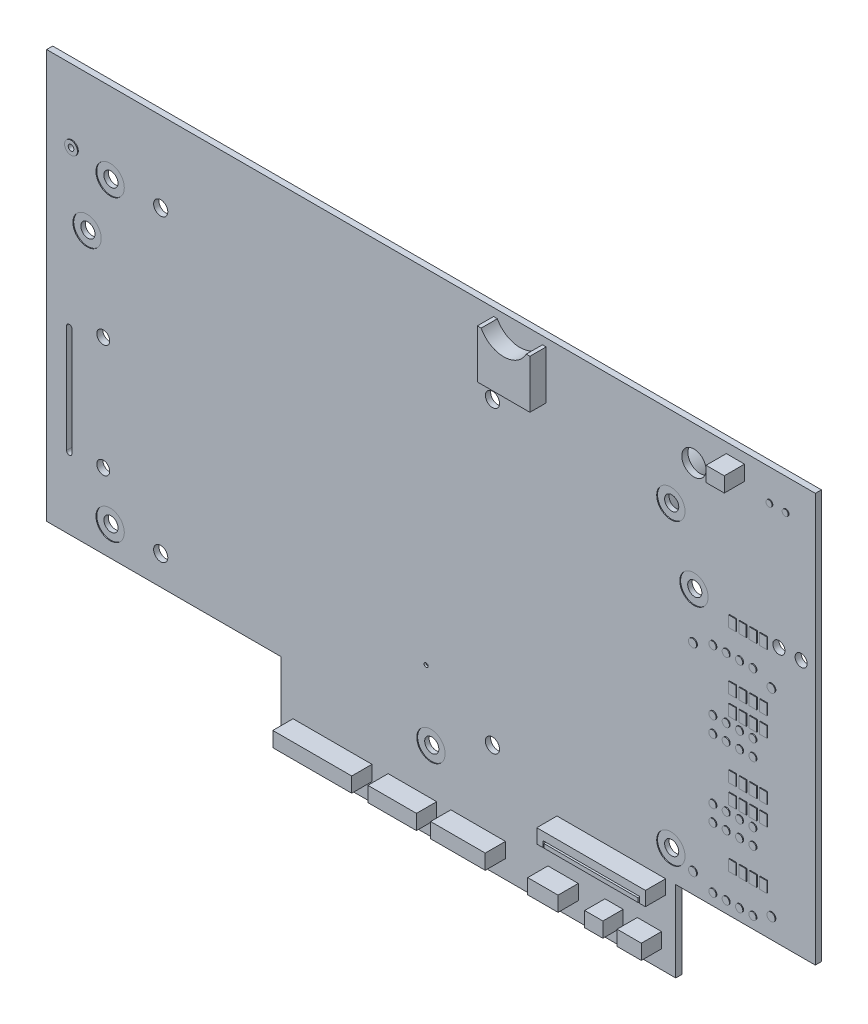
SolidWorks part; units mm, degrees
ref_plane "Face" through (0, 0, 0) normal (0, 0, 1) x (1, 0, 0)
ref_plane "Dessus" through (0, 0, 0) normal (0, 1, 0) x (1, 0, 0)
ref_plane "Droite" through (0, 0, 0) normal (1, 0, 0) x (0, 0, -1)
sketch "Esquisse1" plane through (0, 0, 0) normal (0, 0, 1) x (1, 0, 0)
  line L2 (122.1423, -27.4132) -> (122.1423, 73.5868)
  line L4 (-67.8577, 73.5868) -> (-67.8577, -27.4132)
  line L8 (122.1423, 73.5868) -> (-67.8577, 73.5868)
  line L9 (-67.8577, -27.4132) -> (-9.9458, -27.4132)
  line L10 (-9.9458, -27.4132) -> (-9.9458, -47.4132)
  line L11 (-9.9458, -47.4132) -> (87.6423, -47.4132)
  line L12 (87.6423, -47.4132) -> (87.6423, -27.4132)
  line L13 (87.6423, -27.4132) -> (122.1423, -27.4132)
extrude "Base-Extrusion" add sketch "Esquisse1" along normal blind 1.5
sketch "Esquisse2" plane through (0, 0, 0) normal (0, 0, -1) x (-1, 0, 0)
  circle A0 centre (-86.4423, 53.5868) radius 1.75
  circle A1 centre (52.1577, 53.5868) radius 1.75
  circle A2 centre (52.1577, -20.2132) radius 1.75
  circle A3 centre (-86.4423, -20.2132) radius 1.75
  dimension "D1" = 3.5
  dimension "D2" = 3.5
  dimension "D3" = 3.5
  dimension "D4" = 3.5
extrude "Enlèv. mat.-Extru.1" cut sketch "Esquisse2" against normal blind 2
sketch "Esquisse5" plane through (0, 0, 1.5) normal (0, 0, 1) x (1, 0, 0)
  line L0 (122.1423, -27.4132) -> (122.1423, 73.5868) construction
  line L2 (27.1423, 73.0868) -> (27.1423, -57.4247) construction
  line L3 (122.1423, 73.5868) -> (-67.8577, 73.5868) construction
  circle A0 centre (92.1423, 38.0868) radius 1.75
  circle A1 centre (-57.8577, 39.8368) radius 1.75
  circle A2 centre (27.1423, -27.9132) radius 1.75
  dimension "D1" = 30
  dimension "D3" = 3.5
  dimension "D4" = 66
  dimension "D5" = 3.5
  dimension "D6" = 3.5
  dimension "D2" = 35.5
extrude "Enlèv. mat.-Extru.2" cut sketch "Esquisse5" against normal blind 3
sketch "Esquisse7" plane through (0, 0, 0) normal (0, 0, -1) x (-1, 0, 0)
  line L0 (-73.1423, 95.3031) -> (-73.1423, -81.5415) construction
  line L1 (-122.1423, -27.4132) -> (-122.1423, 73.5868) construction
  line L2 (-45.1037, 46.0868) -> (-133.1932, 46.0868) construction
  line L4 (-122.1423, 73.5868) -> (67.8577, 73.5868) construction
  circle A0 centre (-73.1423, 46.0868) radius 8
  dimension "D4" = 16
  dimension "D2" = 27.5
  dimension "D1" = 49
extrude "Boss.-Extru.1" add sketch "Esquisse7" along normal blind 14.5
sketch "Esquisse10" plane through (0, 0, 1.5) normal (0, 0, 1) x (1, 0, 0)
  circle A0 centre (25.9423, -11.2859) radius 0.5
extrude "Enlèv. mat.-Extru.4" cut sketch "Esquisse10" against normal blind 0.5
sketch "Esquisse15" plane through (0, 0, 1.5) normal (0, 0, 1) x (1, 0, 0)
  line L0 (43.5486, 71.6579) -> (42.6021, 71.6579)
  line L2 (55.6021, 71.6579) -> (55.6021, 59.6579)
  line L3 (42.6021, 71.6579) -> (42.6021, 59.6579)
  line L4 (42.6021, 59.6579) -> (55.6021, 59.6579)
  line L6 (55.6021, 71.6579) -> (54.6958, 71.6579)
  arc A1 (43.5486, 71.6579) -> (54.6958, 71.6579) centre (49.1222, 74.5868) ccw
  dimension "D2" = 6.2963
  dimension "D1" = 13
  dimension "D3" = 14.9289
extrude "Boss.-Extru.6" add sketch "Esquisse15" along normal blind 4
sketch "Esquisse16" plane through (0, 0, 1.5) normal (0, 0, 1) x (1, 0, 0)
  line L0 (58.2923, -30.9132) -> (59.7923, -30.9132)
  line L1 (85.1423, -30.9132) -> (85.1423, -27.4132)
  line L2 (58.2923, -30.9132) -> (58.2923, -27.4132)
  line L3 (58.2923, -27.4132) -> (85.1423, -27.4132)
  line L6 (59.7923, -30.9132) -> (59.7923, -29.4132)
  line L7 (59.7923, -29.4132) -> (83.6423, -29.4132)
  line L8 (83.6423, -29.4132) -> (83.6423, -30.9132)
  line L9 (60.0541, -30.9132) -> (60.0541, -29.9132)
  line L10 (60.0541, -29.9132) -> (83.3602, -29.9132)
  line L11 (83.3602, -29.9132) -> (83.3602, -30.9132)
  line L12 (60.0541, -30.9132) -> (83.3602, -30.9132)
  line L13 (83.6423, -30.9132) -> (85.1423, -30.9132)
  line L14 (-9.9458, -47.4132) -> (87.6423, -47.4132) construction
  line L15 (87.6423, -47.4132) -> (87.6423, -27.4132) construction
  dimension "D1" = 26.85
  dimension "D3" = 3.5
  dimension "D4" = 2.5
  dimension "D5" = 1.5
  dimension "D6" = 1.5
  dimension "D7" = 1
  dimension "D8" = 2
  dimension "D9" = 16.5
extrude "Boss.-Extru.7" add sketch "Esquisse16" along normal blind 5
sketch "Esquisse17" plane through (0, 0, 0) normal (0, 0, -1) x (-1, 0, 0)
  circle A0 centre (-27.1423, -24.4132) radius 8
  circle A1 centre (-92.1423, 41.5868) radius 8
  circle A2 centre (57.8577, 43.3368) radius 8
extrude "Enlèv. mat.-Extru.6" cut sketch "Esquisse17" against normal blind 0.2
sketch "Esquisse18" plane through (0, 0, 0) normal (0, 0, -1) x (-1, 0, 0)
  circle A0 centre (-86.4423, 53.5868) radius 3.5
  circle A3 centre (52.1577, 53.5868) radius 3.5
  circle A4 centre (52.1577, -20.2132) radius 3.5
  circle A7 centre (-86.4423, -20.2132) radius 3.5
extrude "Enlèv. mat.-Extru.7" cut sketch "Esquisse18" against normal blind 0.2
sketch "Esquisse19" plane through (0, 0, 1.5) normal (0, 0, 1) x (1, 0, 0)
  circle A0 centre (-52.1577, 53.5868) radius 3.5
  circle A3 centre (86.4423, 53.5868) radius 3.5
  circle A4 centre (92.1423, 38.0868) radius 3.5
  circle A5 centre (86.4423, -20.2132) radius 3.5
  circle A7 centre (27.1423, -27.9132) radius 3.5
  circle A9 centre (-52.1577, -20.2132) radius 3.5
  circle A10 centre (-57.8577, 39.8368) radius 3.5
extrude "Enlèv. mat.-Extru.8" cut sketch "Esquisse19" against normal blind 0.2
sketch "Esquisse22" plane through (0, 0, 1.5) normal (0, 0, 1) x (1, 0, 0)
  line L0 (56.0542, -39.2132) -> (56.0542, -42.9132)
  line L2 (56.0542, -39.2132) -> (63.5542, -39.2132)
  line L3 (56.0542, -42.9132) -> (63.5542, -42.9132)
  line L4 (63.5542, -39.2132) -> (63.5542, -42.9132)
  line L5 (100.1423, 71.0868) -> (100.1423, 67.3868)
  line L6 (78.1423, -39.2132) -> (78.1423, -42.9132)
  line L7 (84.1423, -39.2132) -> (84.1423, -42.9132)
  line L8 (78.1423, -39.2132) -> (84.1423, -39.2132)
  line L9 (78.1423, -42.9132) -> (84.1423, -42.9132)
  line L10 (100.1423, 71.0868) -> (104.6423, 71.0868)
  line L11 (100.1423, 67.3868) -> (104.6423, 67.3868)
  line L12 (104.6423, 71.0868) -> (104.6423, 67.3868)
  line L13 (122.1423, -27.4132) -> (122.1423, 73.5868) construction
  line L17 (32.0542, -39.2132) -> (32.0542, -42.9132)
  line L18 (32.0542, -39.2132) -> (45.5542, -39.2132)
  line L19 (32.0542, -42.9132) -> (45.5542, -42.9132)
  line L20 (45.5542, -39.2132) -> (45.5542, -42.9132)
  line L21 (70.1423, -39.2132) -> (70.1423, -42.9132)
  line L22 (70.1423, -39.2132) -> (74.6423, -39.2132)
  line L23 (70.1423, -42.9132) -> (74.6423, -42.9132)
  line L24 (74.6423, -39.2132) -> (74.6423, -42.9132)
  line L25 (28.5542, -39.2132) -> (16.5542, -39.2132)
  line L26 (28.5542, -39.2132) -> (28.5542, -42.9132)
  line L27 (28.5542, -42.9132) -> (16.5542, -42.9132)
  line L28 (16.5542, -39.2132) -> (16.5542, -42.9132)
  line L29 (122.1423, 73.5868) -> (-67.8577, 73.5868) construction
  line L30 (12.5542, -42.9132) -> (-6.9458, -42.9132)
  line L31 (12.5542, -42.9132) -> (12.5542, -39.2132)
  line L32 (12.5542, -39.2132) -> (-6.9458, -39.2132)
  line L33 (-6.9458, -42.9132) -> (-6.9458, -39.2132)
  line L34 (87.6423, -47.4132) -> (87.6423, -27.4132) construction
  line L35 (-9.9458, -27.4132) -> (-9.9458, -47.4132) construction
  dimension "D23" = 55.5
  dimension "D3" = 13
  dimension "D4" = 7.5
  dimension "D7" = 3.7
  dimension "D8" = 3.7
  dimension "D9" = 22
  dimension "D11" = 2.5
  dimension "D12" = 4.5
  dimension "D13" = 13.5
  dimension "D15" = 4.5
  dimension "D16" = 22.5
  dimension "D17" = 12
  dimension "D19" = 19.5
  dimension "D21" = 3.5
  dimension "D22" = 38.5
  dimension "D24" = 73.5
  dimension "D6" = 6
extrude "Extrusion1" add sketch "Esquisse22" along normal blind 5
sketch "Esquisse24" plane through (0, 0, 1.5) normal (0, 0, 1) x (1, 0, 0)
  line L0 (105.6777, 36.0868) -> (120.987, 36.0868) construction
  line L1 (87.6423, -27.4132) -> (122.1423, -27.4132) construction
  line L5 (115.8923, 42.3353) -> (115.8923, 32.6178) construction
  line L6 (122.1423, -27.4132) -> (122.1423, 73.5868) construction
  arc A0 (113.1423, 37.5868) -> (113.1423, 34.5868) centre (113.1423, 36.0868) ccw
  arc A1 (118.6423, 34.5868) -> (118.6423, 37.5868) centre (118.6423, 36.0868) ccw
  arc A2 (113.1423, 37.5868) -> (113.1423, 34.5868) centre (113.1423, 36.0868) cw
  arc A3 (118.6423, 37.5868) -> (118.6423, 34.5868) centre (118.6423, 36.0868) ccw
  dimension "D3" = 63.5
  dimension "D2" = 6.25
  dimension "D4" = 5.5
extrude "Enlèv. mat.-Extru.11" cut sketch "Esquisse24" against normal blind 3
sketch "Esquisse28" plane through (0, 0, 1.5) normal (0, 0, 1) x (1, 0, 0)
  line L4 (110.8923, 65.8868) -> (114.8923, 65.8868) construction
  line L5 (112.8923, 71.5211) -> (112.8923, 60.7702) construction
  circle A0 centre (110.8923, 65.8868) radius 0.75
  circle A2 centre (114.8923, 65.8868) radius 0.75
  dimension "D2" = 1.5
  dimension "D4" = 1.5
  dimension "D3" = 4
sketch "Esquisse29" plane through (0, 0, 1.5) normal (0, 0, 1) x (1, 0, 0)
  line L0 (96.9117, 28.5368) -> (100.2117, 28.5368) construction
  line L1 (96.9117, 28.5368) -> (96.9117, 13.5368) construction
  line L2 (96.9117, 9.5368) -> (100.2117, 9.5368) construction
  line L3 (96.9117, 9.5368) -> (96.9117, -5.4632) construction
  line L4 (96.9117, -9.4632) -> (100.2117, -9.4632) construction
  line L5 (96.9117, -9.4632) -> (96.9117, -24.4632) construction
  circle A0 centre (96.9117, 28.5368) radius 0.9
  circle A1 centre (100.2117, 28.5368) radius 0.9
  circle A2 centre (103.5117, 28.5368) radius 0.9
  circle A3 centre (106.8117, 28.5368) radius 0.9
  circle A4 centre (96.9117, 13.5368) radius 0.9
  circle A5 centre (100.2117, 13.5368) radius 0.9
  circle A6 centre (103.5117, 13.5368) radius 0.9
  circle A7 centre (106.8117, 13.5368) radius 0.9
  circle A8 centre (96.9117, 9.5368) radius 0.9
  circle A9 centre (100.2117, 9.5368) radius 0.9
  circle A10 centre (103.5117, 9.5368) radius 0.9
  circle A11 centre (106.8117, 9.5368) radius 0.9
  circle A12 centre (96.9117, -5.4632) radius 0.9
  circle A13 centre (100.2117, -5.4632) radius 0.9
  circle A14 centre (103.5117, -5.4632) radius 0.9
  circle A15 centre (106.8117, -5.4632) radius 0.9
  circle A16 centre (96.9117, -9.4632) radius 0.9
  circle A17 centre (100.2117, -9.4632) radius 0.9
  circle A18 centre (103.5117, -9.4632) radius 0.9
  circle A19 centre (106.8117, -9.4632) radius 0.9
  circle A20 centre (96.9117, -24.4632) radius 0.9
  circle A21 centre (100.2117, -24.4632) radius 0.9
  circle A22 centre (103.5117, -24.4632) radius 0.9
  circle A23 centre (106.8117, -24.4632) radius 0.9
  dimension "D1" = 90
extrude "Extrusion3" add sketch "Esquisse29" along normal blind 0.2
sketch "Esquisse31" plane through (0, 0, 1.5) normal (0, 0, 1) x (1, 0, 0)
  line L0 (100.9223, -0.9608) -> (102.7223, -0.9608)
  line L1 (100.9223, -0.9608) -> (100.9223, -3.6608)
  line L2 (102.7223, -0.9608) -> (102.7223, -3.6608)
  line L3 (100.9223, -3.6608) -> (102.7223, -3.6608)
  line L4 (101.8223, -1.4132) -> (101.8223, -2.7934) construction
  line L6 (103.4623, -0.9608) -> (105.2623, -0.9608)
  line L7 (103.4623, -0.9608) -> (103.4623, -3.6608)
  line L8 (105.2623, -0.9608) -> (105.2623, -3.6608)
  line L9 (103.4623, -3.6608) -> (105.2623, -3.6608)
  line L10 (104.3623, -1.4132) -> (104.3623, -2.7934) construction
  line L11 (106.0023, -0.9608) -> (107.8023, -0.9608)
  line L12 (106.0023, -0.9608) -> (106.0023, -3.6608)
  line L13 (107.8023, -0.9608) -> (107.8023, -3.6608)
  line L14 (106.0023, -3.6608) -> (107.8023, -3.6608)
  line L15 (106.9023, -1.4132) -> (106.9023, -2.7934) construction
  line L16 (108.5423, -0.9608) -> (110.3423, -0.9608)
  line L17 (108.5423, -0.9608) -> (108.5423, -3.6608)
  line L18 (110.3423, -0.9608) -> (110.3423, -3.6608)
  line L19 (108.5423, -3.6608) -> (110.3423, -3.6608)
  line L20 (109.4423, -1.4132) -> (109.4423, -2.7934) construction
  line L21 (100.9223, -15.1608) -> (102.7223, -15.1608)
  line L22 (100.9223, -15.1608) -> (100.9223, -17.8608)
  line L23 (102.7223, -15.1608) -> (102.7223, -17.8608)
  line L24 (100.9223, -17.8608) -> (102.7223, -17.8608)
  line L25 (101.8223, -15.6132) -> (101.8223, -16.9934) construction
  line L26 (103.4623, -15.1608) -> (105.2623, -15.1608)
  line L27 (103.4623, -15.1608) -> (103.4623, -17.8608)
  line L28 (105.2623, -15.1608) -> (105.2623, -17.8608)
  line L29 (103.4623, -17.8608) -> (105.2623, -17.8608)
  line L30 (104.3623, -15.6132) -> (104.3623, -16.9934) construction
  line L31 (106.0023, -15.1608) -> (107.8023, -15.1608)
  line L32 (106.0023, -15.1608) -> (106.0023, -17.8608)
  line L33 (107.8023, -15.1608) -> (107.8023, -17.8608)
  line L34 (106.0023, -17.8608) -> (107.8023, -17.8608)
  line L35 (106.9023, -15.6132) -> (106.9023, -16.9934) construction
  line L36 (108.5423, -15.1608) -> (110.3423, -15.1608)
  line L37 (108.5423, -15.1608) -> (108.5423, -17.8608)
  line L38 (110.3423, -15.1608) -> (110.3423, -17.8608)
  line L39 (108.5423, -17.8608) -> (110.3423, -17.8608)
  line L40 (109.4423, -15.6132) -> (109.4423, -16.9934) construction
  line L41 (100.9223, -0.9608) -> (103.4623, -0.9608) construction
  line L42 (100.9223, -0.9608) -> (100.9223, -15.1608) construction
  line L43 (100.9223, 18.0392) -> (102.7223, 18.0392)
  line L44 (100.9223, 18.0392) -> (100.9223, 15.3392)
  line L45 (102.7223, 18.0392) -> (102.7223, 15.3392)
  line L46 (100.9223, 15.3392) -> (102.7223, 15.3392)
  line L47 (103.4623, 18.0392) -> (105.2623, 18.0392)
  line L48 (103.4623, 18.0392) -> (103.4623, 15.3392)
  line L49 (105.2623, 18.0392) -> (105.2623, 15.3392)
  line L50 (103.4623, 15.3392) -> (105.2623, 15.3392)
  line L51 (106.0023, 18.0392) -> (107.8023, 18.0392)
  line L52 (106.0023, 18.0392) -> (106.0023, 15.3392)
  line L53 (107.8023, 18.0392) -> (107.8023, 15.3392)
  line L54 (106.0023, 15.3392) -> (107.8023, 15.3392)
  line L55 (108.5423, 18.0392) -> (110.3423, 18.0392)
  line L56 (108.5423, 18.0392) -> (108.5423, 15.3392)
  line L57 (110.3423, 18.0392) -> (110.3423, 15.3392)
  line L58 (108.5423, 15.3392) -> (110.3423, 15.3392)
  line L59 (100.9223, 3.8392) -> (102.7223, 3.8392)
  line L60 (100.9223, 3.8392) -> (100.9223, 1.1392)
  line L61 (102.7223, 3.8392) -> (102.7223, 1.1392)
  line L62 (100.9223, 1.1392) -> (102.7223, 1.1392)
  line L63 (103.4623, 3.8392) -> (105.2623, 3.8392)
  line L64 (103.4623, 3.8392) -> (103.4623, 1.1392)
  line L65 (105.2623, 3.8392) -> (105.2623, 1.1392)
  line L66 (103.4623, 1.1392) -> (105.2623, 1.1392)
  line L67 (106.0023, 3.8392) -> (107.8023, 3.8392)
  line L68 (106.0023, 3.8392) -> (106.0023, 1.1392)
  line L69 (107.8023, 3.8392) -> (107.8023, 1.1392)
  line L70 (106.0023, 1.1392) -> (107.8023, 1.1392)
  line L71 (108.5423, 3.8392) -> (110.3423, 3.8392)
  line L72 (108.5423, 3.8392) -> (108.5423, 1.1392)
  line L73 (110.3423, 3.8392) -> (110.3423, 1.1392)
  line L74 (108.5423, 1.1392) -> (110.3423, 1.1392)
  line L75 (101.8223, 17.5868) -> (101.8223, 16.2066) construction
  line L76 (104.3623, 17.5868) -> (104.3623, 16.2066) construction
  line L77 (106.9023, 17.5868) -> (106.9023, 16.2066) construction
  line L78 (109.4423, 17.5868) -> (109.4423, 16.2066) construction
  line L79 (101.8223, 3.3868) -> (101.8223, 2.0066) construction
  line L80 (104.3623, 3.3868) -> (104.3623, 2.0066) construction
  line L81 (106.9023, 3.3868) -> (106.9023, 2.0066) construction
  line L82 (109.4423, 3.3868) -> (109.4423, 2.0066) construction
  line L83 (100.9223, 18.0392) -> (103.4623, 18.0392) construction
  line L84 (100.9223, 18.0392) -> (100.9223, 3.8392) construction
  line L85 (100.9223, 37.0392) -> (102.7223, 37.0392)
  line L86 (100.9223, 37.0392) -> (100.9223, 34.3392)
  line L87 (102.7223, 37.0392) -> (102.7223, 34.3392)
  line L88 (100.9223, 34.3392) -> (102.7223, 34.3392)
  line L89 (103.4623, 37.0392) -> (105.2623, 37.0392)
  line L90 (103.4623, 37.0392) -> (103.4623, 34.3392)
  line L91 (105.2623, 37.0392) -> (105.2623, 34.3392)
  line L92 (103.4623, 34.3392) -> (105.2623, 34.3392)
  line L93 (106.0023, 37.0392) -> (107.8023, 37.0392)
  line L94 (106.0023, 37.0392) -> (106.0023, 34.3392)
  line L95 (107.8023, 37.0392) -> (107.8023, 34.3392)
  line L96 (106.0023, 34.3392) -> (107.8023, 34.3392)
  line L97 (108.5423, 37.0392) -> (110.3423, 37.0392)
  line L98 (108.5423, 37.0392) -> (108.5423, 34.3392)
  line L99 (110.3423, 37.0392) -> (110.3423, 34.3392)
  line L100 (108.5423, 34.3392) -> (110.3423, 34.3392)
  line L101 (100.9223, 22.8392) -> (102.7223, 22.8392)
  line L102 (100.9223, 22.8392) -> (100.9223, 20.1392)
  line L103 (102.7223, 22.8392) -> (102.7223, 20.1392)
  line L104 (100.9223, 20.1392) -> (102.7223, 20.1392)
  line L105 (103.4623, 22.8392) -> (105.2623, 22.8392)
  line L106 (103.4623, 22.8392) -> (103.4623, 20.1392)
  line L107 (105.2623, 22.8392) -> (105.2623, 20.1392)
  line L108 (103.4623, 20.1392) -> (105.2623, 20.1392)
  line L109 (106.0023, 22.8392) -> (107.8023, 22.8392)
  line L110 (106.0023, 22.8392) -> (106.0023, 20.1392)
  line L111 (107.8023, 22.8392) -> (107.8023, 20.1392)
  line L112 (106.0023, 20.1392) -> (107.8023, 20.1392)
  line L113 (108.5423, 22.8392) -> (110.3423, 22.8392)
  line L114 (108.5423, 22.8392) -> (108.5423, 20.1392)
  line L115 (110.3423, 22.8392) -> (110.3423, 20.1392)
  line L116 (108.5423, 20.1392) -> (110.3423, 20.1392)
  line L117 (101.8223, 36.5868) -> (101.8223, 35.2066) construction
  line L118 (104.3623, 36.5868) -> (104.3623, 35.2066) construction
  line L119 (106.9023, 36.5868) -> (106.9023, 35.2066) construction
  line L120 (109.4423, 36.5868) -> (109.4423, 35.2066) construction
  line L121 (101.8223, 22.3868) -> (101.8223, 21.0066) construction
  line L122 (104.3623, 22.3868) -> (104.3623, 21.0066) construction
  line L123 (106.9023, 22.3868) -> (106.9023, 21.0066) construction
  line L124 (109.4423, 22.3868) -> (109.4423, 21.0066) construction
  line L125 (100.9223, 37.0392) -> (103.4623, 37.0392) construction
  line L126 (100.9223, 37.0392) -> (100.9223, 22.8392) construction
  dimension "D1" = 1.8
  dimension "D2" = 2.7
  dimension "D3" = 90
extrude "Extrusion4" add sketch "Esquisse31" along normal blind 0.2
sketch "Esquisse32" plane through (0, 0, 1.5) normal (0, 0, 1) x (1, 0, 0)
  line L1 (91.0873, 26.5723) -> (92.4818, 26.5723) construction
  line L2 (91.9971, 27.5096) -> (91.9971, 26.208) construction
  circle A0 centre (91.9971, 26.5723) radius 1
  circle A1 centre (111.3871, 26.5723) radius 1
  circle A2 centre (91.9937, -22.356) radius 1
  circle A3 centre (111.3871, -22.356) radius 1
extrude "Extrusion5" add sketch "Esquisse32" along normal blind 0.2
sketch "Esquisse33" plane through (0, 0, 0) normal (0, 0, -1) x (-1, 0, 0)
  circle A0 centre (-42.3423, -20.2132) radius 1.75
  circle A1 centre (-42.3423, 53.7868) radius 1.75
  circle A2 centre (39.6577, -20.2132) radius 1.75
  circle A3 centre (39.6577, 53.7868) radius 1.75
  dimension "D1" = 3.5
extrude "Enlèv. mat.-Extru.17" cut sketch "Esquisse33" against normal blind 4
sketch "Esquisse34" plane through (0, 0, 0) normal (0, 0, -1) x (-1, 0, 0)
  circle A0 centre (-42.3423, 53.7868) radius 3.5
  circle A1 centre (-42.3423, -20.2132) radius 3.5
  circle A2 centre (39.6577, -20.2132) radius 3.5
  circle A3 centre (39.6577, 53.7868) radius 3.5
extrude "Enlèv. mat.-Extru.18" cut sketch "Esquisse34" against normal blind 0.2
extrude "Extrusion7" add sketch "Esquisse28" along normal blind 0.2
sketch "Esquisse36" plane through (0, 0, 1.5) normal (0, 0, 1) x (1, 0, 0)
  line L0 (-62.9327, 16.8868) -> (-62.9327, -9.7632)
  line L2 (-67.8577, -27.4132) -> (-9.9458, -27.4132) construction
  line L3 (-61.5827, 16.8868) -> (-61.5827, -9.7632)
  line L4 (-62.2577, 23.3878) -> (-62.2577, -22.61) construction
  line L5 (-67.8577, 73.5868) -> (-67.8577, -27.4132) construction
  arc A0 (-62.9327, 16.8868) -> (-61.5827, 16.8868) centre (-62.2577, 16.8868) cw
  arc A1 (-62.9327, -9.7632) -> (-61.5827, -9.7632) centre (-62.2577, -9.7632) ccw
  dimension "D4" = 26.65
  dimension "D1" = 5.6
  dimension "D2" = 1.35
  dimension "D5" = 17.65
extrude "Enlèv. mat.-Extru.19" cut sketch "Esquisse36" against normal blind 10
sketch "Esquisse37" plane through (0, 0, 0) normal (0, 0, -1) x (-1, 0, 0)
  circle A0 centre (61.6239, 55.7786) radius 1.6
extrude "Extrusion8" add sketch "Esquisse37" along normal blind 0.2
sketch "Esquisse38" plane through (0, 0, -0.2) normal (0, 0, -1) x (-1, 0, 0)
  circle A0 centre (61.6239, 55.7786) radius 0.7
extrude "Enlèv. mat.-Extru.20" cut sketch "Esquisse38" against normal blind 3
sketch "Esquisse39" plane through (0, 0, 1.5) normal (0, 0, 1) x (1, 0, 0)
  circle A0 centre (-61.6239, 55.7786) radius 1.6
  circle A1 centre (-61.6239, 55.7786) radius 0.7
extrude "Extrusion9" add sketch "Esquisse39" along normal blind 0.2
sketch "Esquisse40" plane through (0, 0, 0) normal (0, 0, -1) x (-1, 0, 0)
  line L0 (53.8577, 23.9783) -> (53.8577, -23.8627) construction
  line L1 (67.8577, 73.5868) -> (67.8577, -27.4132) construction
  line L3 (67.8577, -27.4132) -> (9.9458, -27.4132) construction
  circle A0 centre (53.8577, 18.9868) radius 1.6
  circle A1 centre (53.8577, -8.9132) radius 1.6
  dimension "D2" = 3.2
  dimension "D3" = 3.2
  dimension "D1" = 14
  dimension "D5" = 27.9
  dimension "D6" = 18.5
extrude "Enlèv. mat.-Extru.21" cut sketch "Esquisse40" against normal blind 10
sketch "Esquisse41" plane through (0, 0, 1.5) normal (0, 0, 1) x (1, 0, 0)
  line L0 (122.1423, -27.4132) -> (122.1423, 73.5868) construction
  line L2 (122.1423, 73.5868) -> (-67.8577, 73.5868) construction
  circle A0 centre (92.1423, 65.0868) radius 3
  dimension "D1" = 30
  dimension "D3" = 8.5
extrude "Enlèv. mat.-Extru.22" cut sketch "Esquisse41" against normal blind 10
